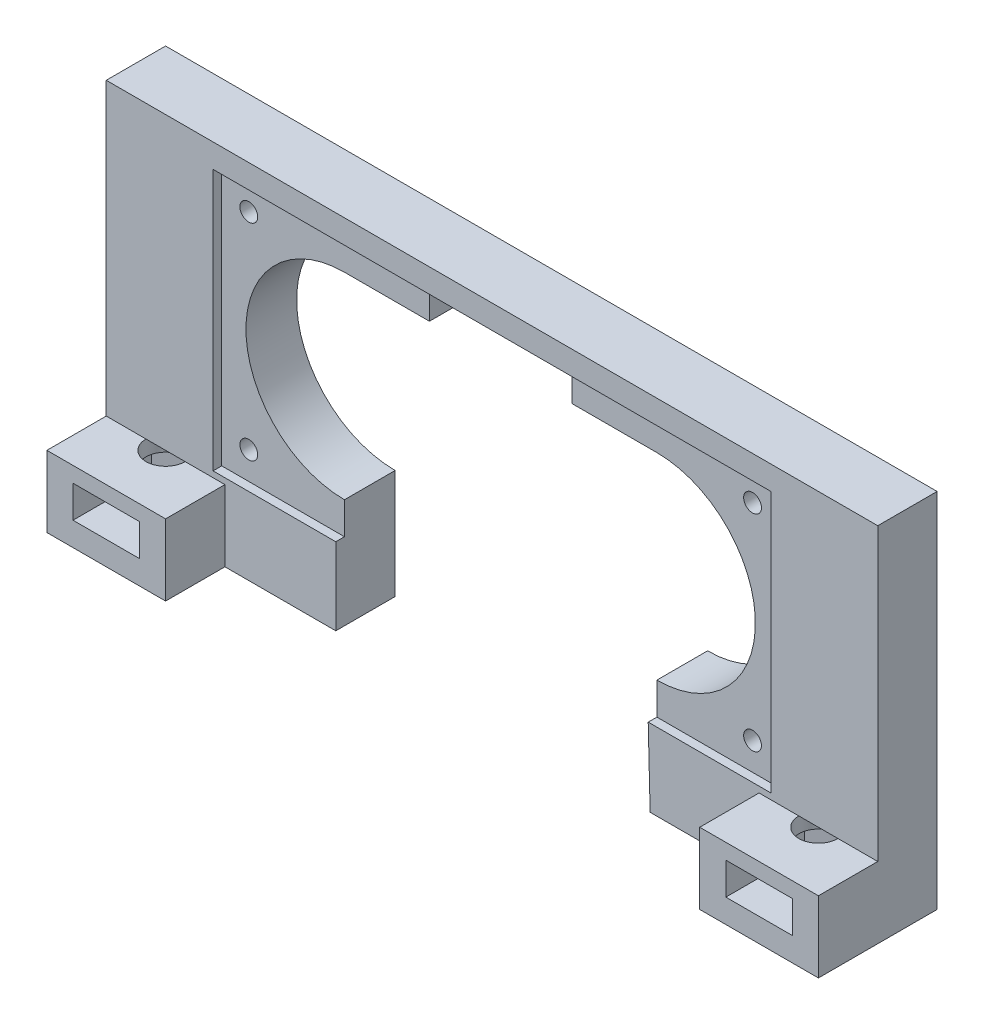
SolidWorks part; units mm, degrees
ref_plane "Спереди" through (0, 0, 0) normal (0, 0, 1) x (1, 0, 0)
ref_plane "Сверху" through (0, 0, 0) normal (0, 1, 0) x (1, 0, 0)
ref_plane "Справа" through (0, 0, 0) normal (1, 0, 0) x (0, 0, -1)
sketch "Эскиз1" plane through (0, 0, 0) normal (0, 0, 1) x (1, 0, 0)
  line L0 (13.16, 8.3) -> (6, 8.3)
  line L1 (13.16, -8.3) -> (13.16, -11)
  line L2 (6, 8.3) -> (6, 11)
  line L3 (-1000, 0) -> (49000, 0) construction
  line L4 (0, -1000) -> (0, 49000) construction
  line L5 (0, 1000) -> (0, -49000) construction
  line L6 (-6, 11) -> (6, 11)
  line L7 (-13.16, -11) -> (13.16, -11)
  line L9 (1000, 0) -> (-49000, 0) construction
  line L13 (-6, 8.3) -> (-6, 11)
  line L14 (-13.16, -8.3) -> (-13.16, -11)
  line L15 (-13.16, 8.3) -> (-6, 8.3)
  line L17 (-23.5, -11) -> (23.5, -11) construction
  line L18 (-23.5, -11) -> (-23.5, 11) construction
  line L19 (-23.5, 11) -> (23.5, 11) construction
  line L20 (23.5, -11) -> (23.5, 11) construction
  line L21 (-23.5, -11) -> (23.5, 11) construction
  line L22 (-23.5, 11) -> (23.5, -11) construction
  arc A0 (13.16, 8.3) -> (13.16, -8.3) centre (13.16, 0) cw
  circle A1 centre (21.22, 8.675) radius 0.75
  circle A2 centre (21.22, -8.675) radius 0.75
  circle A3 centre (21.22, 8.675) radius 0.75
  circle A4 centre (21.22, -8.675) radius 0.75
  circle A5 centre (-21.22, -8.675) radius 0.75
  circle A6 centre (-21.22, 8.675) radius 0.75
  circle A7 centre (-21.22, -8.675) radius 0.75
  circle A8 centre (-21.22, 8.675) radius 0.75
  arc A9 (-13.16, 8.3) -> (-13.16, -8.3) centre (-13.16, 0) ccw
  point P39 (0, 0)
  dimension "D1" = 8.3
  dimension "D6" = 1.5
  dimension "D2" = 13.16
  dimension "D3" = 6
  dimension "D4" = 11
  dimension "D5" = 11
  dimension "D7" = 21.22
  dimension "D8" = 8.675
  dimension "D9" = 47
  dimension "D10" = 22
sketch "Эскиз2" plane through (0, 0, 0) normal (0, 0, 1) x (1, 0, 0)
  line L0 (-32.5, 13) -> (32.5, 13)
  line L1 (32.5, 13) -> (32.5, -17.5)
  line L2 (32.5, -17.5) -> (13.3231, -17.5)
  line L3 (13.3231, -17.5) -> (13.16, -11)
  line L4 (13.16, -11) -> (-13.16, -11)
  line L5 (-13.16, -11) -> (-13.16, -17.5)
  line L6 (-13.16, -17.5) -> (-32.5, -17.5)
  line L7 (-32.5, -17.5) -> (-32.5, 13)
  line L8 (0, -201000) -> (0, 249000) construction
  line L9 (-201000, 0) -> (249000, 0) construction
  point P9 (0, 13)
  dimension "D1" = 65
  dimension "D2" = 13
  dimension "D3" = 17.5
extrude "Бобышка-Вытянуть1" add sketch "Эскиз2" along normal blind 5
extrude "Вырез-Вытянуть11" cut sketch "Эскиз1" along normal blind 5 contours A9 L14 L7 L1 A0 L0 L2 L6 L13 L15 | A6 | A5 | A1 | A2
sketch "Эскиз3" plane through (0, 0, 5) normal (0, 0, 1) x (1, 0, 0)
  line L1 (-23.5, -11) -> (23.5, -11)
  line L2 (-23.5, -11) -> (-23.5, 11)
  line L3 (-23.5, 11) -> (23.5, 11)
  line L4 (23.5, -11) -> (23.5, 11)
  line L5 (-23.5, -11) -> (23.5, 11) construction
  line L6 (-23.5, 11) -> (23.5, -11) construction
  point P0 (0, 0)
  dimension "D1" = 47
  dimension "D2" = 22
extrude "Вырез-Вытянуть14" cut sketch "Эскиз3" against normal blind 0.73
sketch "Эскиз4" plane through (0, -17.5, 0) normal (0, -1, 0) x (1, 0, 0)
  line L1 (-32.5, 0) -> (-22.5, 0)
  line L2 (-32.5, 0) -> (-32.5, 10)
  line L3 (-32.5, 10) -> (-22.5, 10)
  line L4 (-22.5, 0) -> (-22.5, 10)
  line L5 (32.5, 0) -> (22.5, 0)
  line L6 (32.5, 0) -> (32.5, 10)
  line L7 (32.5, 10) -> (22.5, 10)
  line L8 (22.5, 0) -> (22.5, 10)
  dimension "D1" = 10
  dimension "D2" = 10
  dimension "D3" = 10
  dimension "D4" = 10
extrude "Бобышка-Вытянуть2" add sketch "Эскиз4" against normal blind 6
sketch "Эскиз5" plane through (0, -17.5, 0) normal (0, -1, 0) x (1, 0, 0)
  line L0 (-32.5, 10) -> (-32.5, 0) construction
  line L1 (32.5, 10) -> (32.5, 0) construction
  line L2 (-22.5, 10) -> (-32.5, 10) construction
  line L3 (32.5, 10) -> (22.5, 10) construction
  circle A0 centre (-27.5, 5) radius 1.65
  circle A1 centre (27.5, 5) radius 1.65
  point P4 (-32.5, 5)
  dimension "D5" = 3.3
  dimension "D6" = 3.3
  dimension "D1" = 5
  dimension "D2" = 5
  dimension "D3" = 5
  dimension "D4" = 5
extrude "Вырез-Вытянуть15" cut sketch "Эскиз5" against normal blind 6
ref_plane "Плоскость1" through (0, -15.5, 0) normal (0, -1, 0) x (-1, 0, 0)
sketch "Эскиз6" plane through (0, -15.5, 0) normal (0, -1, 0) x (-1, 0, 0)
  line L0 (29.15, -5) -> (25.85, -5) construction
  line L1 (30.3, -6.6166) -> (30.3, -10)
  line L2 (30.3, -6.6166) -> (30.3, -3.3834)
  line L3 (30.3, -3.3834) -> (27.5, -1.7668)
  line L4 (27.5, -1.7668) -> (24.7, -3.3834)
  line L5 (24.7, -3.3834) -> (24.7, -6.6166)
  line L6 (22.5, -10) -> (32.5, -10) construction
  line L7 (-29.15, -5) -> (-25.85, -5) construction
  line L8 (-24.7, -6.6166) -> (-24.7, -10)
  line L9 (-24.7, -6.6166) -> (-24.7, -3.3834)
  line L10 (-24.7, -3.3834) -> (-27.5, -1.7668)
  line L11 (-27.5, -1.7668) -> (-30.3, -3.3834)
  line L12 (-30.3, -3.3834) -> (-30.3, -6.6166)
  line L13 (-32.5, -10) -> (-22.5, -10) construction
  line L14 (27.5, -8.2332) -> (30.3, -6.6166) [skipped]
  line L15 (24.7, -6.6166) -> (27.5, -8.2332) [skipped]
  line L16 (30.3, -10) -> (24.7, -10)
  line L17 (24.7, -10) -> (24.7, -6.6166)
  line L18 (-24.7, -10) -> (-30.3, -10)
  line L19 (-27.5, -8.2332) -> (-24.7, -6.6166) [skipped]
  line L20 (-30.3, -6.6166) -> (-27.5, -8.2332) [skipped]
  line L21 (-30.3, -10) -> (-30.3, -6.6166)
  circle A0 centre (27.5, -5) radius 2.8 construction
  circle A1 centre (-27.5, -5) radius 2.8 construction
extrude "Вырез-Вытянуть16" cut sketch "Эскиз6" against normal blind 2.7
sketch "Эскиз7" plane through (0, 0, 0) normal (0, 0, -1) x (-1, 0, 0)
  line L1 (-21.22, 10.5225) -> (-22.82, 9.5988)
  line L2 (-22.82, 9.5988) -> (-22.82, 7.7512)
  line L3 (-22.82, 7.7512) -> (-21.22, 6.8275)
  line L4 (-21.22, 6.8275) -> (-19.62, 7.7512)
  line L5 (-19.62, 7.7512) -> (-19.62, 9.5988)
  line L6 (-19.62, 9.5988) -> (-21.22, 10.5225)
  line L7 (-21.22, -6.8275) -> (-22.82, -7.7512)
  line L8 (-22.82, -7.7512) -> (-22.82, -9.5988)
  line L9 (-22.82, -9.5988) -> (-21.22, -10.5225)
  line L10 (-21.22, -10.5225) -> (-19.62, -9.5988)
  line L11 (-19.62, -9.5988) -> (-19.62, -7.7512)
  line L12 (-19.62, -7.7512) -> (-21.22, -6.8275)
  line L13 (21.22, 10.5225) -> (19.62, 9.5988)
  line L14 (19.62, 9.5988) -> (19.62, 7.7512)
  line L15 (19.62, 7.7512) -> (21.22, 6.8275)
  line L16 (21.22, 6.8275) -> (22.82, 7.7512)
  line L17 (22.82, 7.7512) -> (22.82, 9.5988)
  line L18 (22.82, 9.5988) -> (21.22, 10.5225)
  line L19 (21.22, -6.8275) -> (19.62, -7.7512)
  line L20 (19.62, -7.7512) -> (19.62, -9.5988)
  line L21 (19.62, -9.5988) -> (21.22, -10.5225)
  line L22 (21.22, -10.5225) -> (22.82, -9.5988)
  line L23 (22.82, -9.5988) -> (22.82, -7.7512)
  line L24 (22.82, -7.7512) -> (21.22, -6.8275)
  circle A0 centre (-21.22, 8.675) radius 1.6 construction
  circle A1 centre (-21.22, -8.675) radius 1.6 construction
  circle A2 centre (21.22, 8.675) radius 1.6 construction
  circle A3 centre (21.22, -8.675) radius 1.6 construction
extrude "Вырез-Вытянуть17" cut sketch "Эскиз7" against normal blind 2
